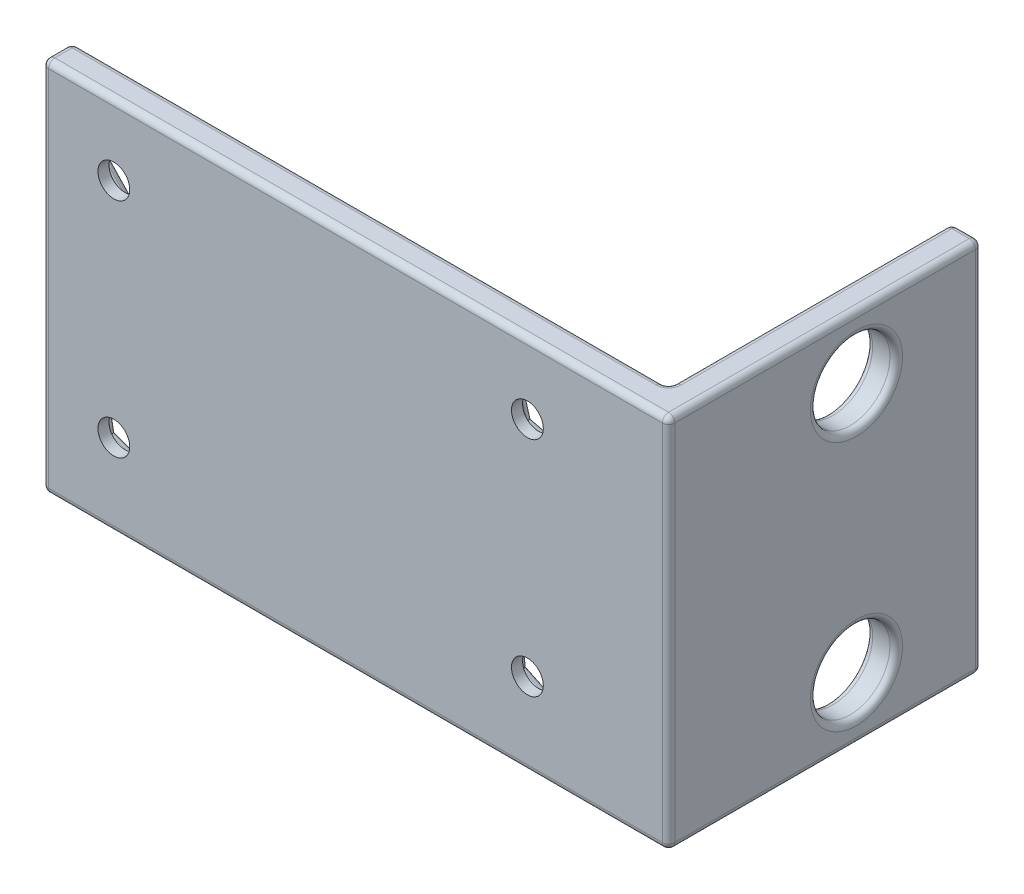
SolidWorks part; units mm, degrees
ref_plane "Front Plane" through (0, 0, 0) normal (0, 0, 1) x (1, 0, 0)
ref_plane "Top Plane" through (0, 0, 0) normal (0, 1, 0) x (1, 0, 0)
ref_plane "Right Plane" through (0, 0, 0) normal (1, 0, 0) x (0, 0, -1)
sketch "Sketch1" plane through (0, 0, 0) normal (0, 1, 0) x (1, 0, 0)
  line L0 (0, 0) -> (0, 22.6188)
  line L1 (0, 22.6188) -> (2.3813, 22.6188)
  line L2 (2.3813, 22.6188) -> (2.3813, -2.3812)
  line L3 (2.3813, -2.3812) -> (-47.6187, -2.3813)
  line L4 (-47.6187, -2.3813) -> (-47.6187, 0)
  line L5 (-47.6187, 0) -> (0, 0)
  dimension "D1" = 2.3813
  dimension "D2" = 25
  dimension "D3" = 50
extrude "Boss-Extrude1" add sketch "Sketch1" along normal blind 30
sketch "Sketch2" plane through (0, 0, 2.3812) normal (0, 0, 1) x (1, 0, 0)
  line L0 (-41.91, 24.379) -> (-8.89, 24.379) construction
  line L1 (-8.89, 24.379) -> (-8.89, 6.599) construction
  line L2 (-8.89, 6.599) -> (-41.91, 6.599) construction
  line L3 (-41.91, 6.599) -> (-41.91, 24.379) construction
  line L4 (-47.6187, 0) -> (2.3813, 0)
  line L5 (2.3813, 0) -> (2.3813, 30)
  line L6 (2.3813, 30) -> (-47.6187, 30)
  line L7 (-47.6187, 30) -> (-47.6187, 0)
  line L8 (-47.6187, 0) -> (2.3813, 0) construction
  line L9 (2.3813, 0) -> (2.3813, 30) construction
  line L10 (2.3813, 30) -> (-47.6187, 30) construction
  line L11 (-47.6187, 30) -> (-47.6187, 0) construction
  circle A1 centre (-41.91, 6.599) radius 1.27
  circle A3 centre (-8.89, 6.599) radius 1.27
  circle A5 centre (-8.89, 24.379) radius 1.27
  circle A7 centre (-41.91, 24.379) radius 1.27
  dimension "D2" = 33.02
  dimension "D3" = 17.78
  dimension "D1" = 0
extrude "Cut-Extrude1" cut sketch "Sketch2" against normal through all
sketch "Sketch3" plane through (2.3813, 0, 0) normal (1, 0, 0) x (0, 0, -1)
  line L4 (-2.3812, 0) -> (22.6188, 0)
  line L5 (22.6188, 0) -> (22.6188, 30)
  line L6 (22.6188, 30) -> (-2.3812, 30)
  line L7 (-2.3812, 30) -> (-2.3812, 0)
  line L8 (-2.3812, 0) -> (22.6188, 0) construction
  line L9 (22.6188, 0) -> (22.6188, 30) construction
  line L10 (22.6188, 30) -> (-2.3812, 30) construction
  line L11 (-2.3812, 30) -> (-2.3812, 0) construction
  circle A0 centre (12.6188, 25) radius 3.175
  circle A1 centre (12.6188, 5) radius 3.175
  point P2 (12.6188, 25)
  point P4 (12.6188, 5)
  dimension "D5" = 6.35
  dimension "D2" = 20
  dimension "D3" = 5
  dimension "D4" = 15
  dimension "D1" = 0
extrude "Cut-Extrude2" cut sketch "Sketch3" against normal through all
fillet "Fillet1" radius 0.5 26 edges at (-47.6187, 15, 2.3813) (-47.6187, 0, 1.1906) (-22.6187, 0, 2.3812) (2.3813, 15, 2.3812) (2.3813, 0, -10.1188) (2.3813, 5, -15.7938) (2.3813, 25, -15.7938) (2.3813, 15, -22.6188) (1.1906, 0, -22.6188) (1.1906, 30, -22.6188) (2.3813, 30, -10.1188) (-22.6187, 30, 2.3812) (-47.6187, 30, 1.1906) (0, 15, -22.6188) (0, 30, -11.3094) (0, 0, -11.3094) (0, 5, -15.7938) (0, 25, -15.7938) (0, 15, 0) (-23.8094, 30, 0) (-47.6187, 15, 0) (-23.8094, 0, 0) (-40.64, 6.599, 0) (-7.62, 6.599, 0) (-7.62, 24.379, 0) (-40.64, 24.379, 0)
sketch "Sketch5" plane through (0, 0, 0) normal (0, 0, -1) x (-1, 0, 0)
  line L1 (10.8039, 22.3748) -> (11.5827, 25.0344)
  line L2 (11.5827, 25.0344) -> (9.6687, 27.0386)
  line L3 (9.6687, 27.0386) -> (6.9761, 26.3833)
  line L4 (6.9761, 26.3833) -> (6.1973, 23.7236)
  line L5 (6.1973, 23.7236) -> (8.1113, 21.7194)
  line L6 (8.1113, 21.7194) -> (10.8039, 22.3748)
  line L7 (11.1708, 5.0249) -> (11.3937, 7.7872)
  line L8 (11.3937, 7.7872) -> (9.1129, 9.3613)
  line L9 (9.1129, 9.3613) -> (6.6092, 8.1732)
  line L10 (6.6092, 8.1732) -> (6.3863, 5.4109)
  line L11 (6.3863, 5.4109) -> (8.6671, 3.8367)
  line L12 (8.6671, 3.8367) -> (11.1708, 5.0249)
  line L13 (39.3037, 5.657) -> (41.4227, 3.8709)
  line L14 (41.4227, 3.8709) -> (44.0289, 4.8129)
  line L15 (44.0289, 4.8129) -> (44.5163, 7.541)
  line L16 (44.5163, 7.541) -> (42.3973, 9.3271)
  line L17 (42.3973, 9.3271) -> (39.7911, 8.3851)
  line L18 (39.7911, 8.3851) -> (39.3037, 5.657)
  line L19 (39.9961, 22.3748) -> (42.6887, 21.7194)
  line L20 (42.6887, 21.7194) -> (44.6027, 23.7236)
  line L21 (44.6027, 23.7236) -> (43.8239, 26.3833)
  line L22 (43.8239, 26.3833) -> (41.1313, 27.0386)
  line L23 (41.1313, 27.0386) -> (39.2173, 25.0344)
  line L24 (39.2173, 25.0344) -> (39.9961, 22.3748)
  circle A0 centre (8.89, 24.379) radius 2.4 construction
  circle A1 centre (8.89, 6.599) radius 2.4 construction
  circle A2 centre (41.91, 6.599) radius 2.4 construction
  circle A3 centre (41.91, 24.379) radius 2.4 construction
  dimension "D1" = 4.8
  dimension "D2" = 4.8
  dimension "D3" = 4.8
  dimension "D4" = 4.8
extrude "Cut-Extrude3" cut sketch "Sketch5" against normal blind 1.5
fillet "Fillet2" radius 0.5 24 edges at (-10.6257, 26.0365, 0) (-8.3224, 26.7109, 0) (-6.5867, 25.0534, 0) (-7.1543, 22.7215, 0) (-9.4576, 22.0471, 0) (-11.1933, 23.7046, 0) (-10.2533, 8.5743, 0) (-7.861, 8.7673, 0) (-6.4978, 6.792, 0) (-7.5267, 4.6238, 0) (-9.919, 4.4308, 0) (-11.2822, 6.406, 0) (-42.7258, 4.3419, 0) (-44.2726, 6.177, 0) (-43.4568, 8.4341, 0) (-41.0942, 8.8561, 0) (-39.5474, 7.0211, 0) (-40.3632, 4.764, 0) (-43.6457, 22.7215, 0) (-44.2133, 25.0534, 0) (-42.4776, 26.7109, 0) (-40.1743, 26.0365, 0) (-39.6067, 23.7046, 0) (-41.3424, 22.0471, 0)
